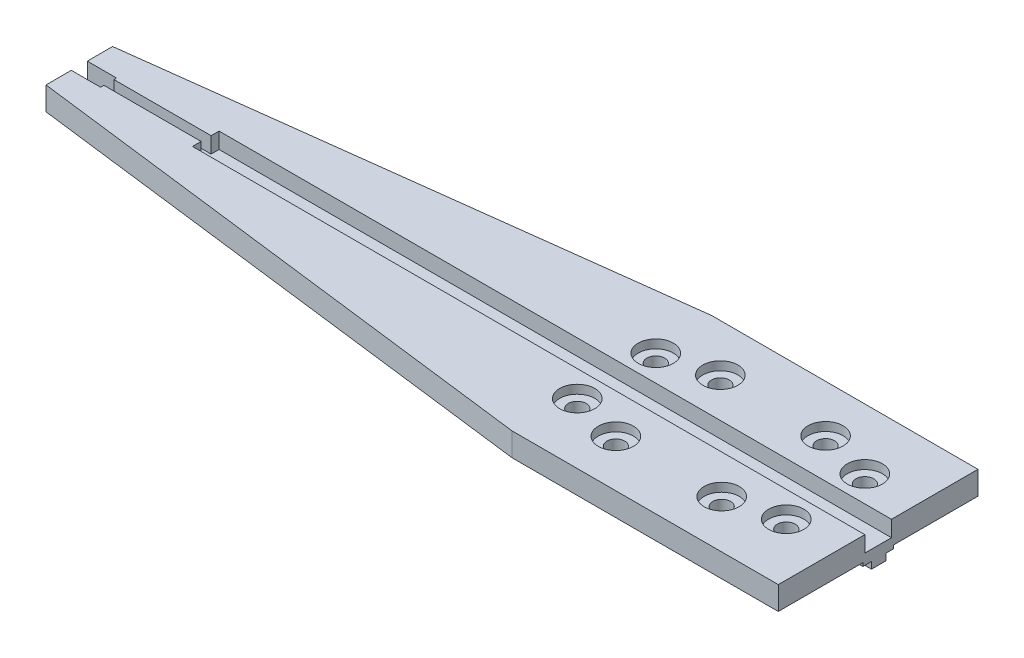
SolidWorks part; units mm, degrees
ref_plane "Front Plane" through (0, 0, 0) normal (0, 0, 1) x (1, 0, 0)
ref_plane "Top Plane" through (0, 0, 0) normal (0, 1, 0) x (1, 0, 0)
ref_plane "Right Plane" through (0, 0, 0) normal (1, 0, 0) x (0, 0, -1)
sketch "Sketch2" plane through (0, 0, 0) normal (1, 0, 0) x (0, 0, -1)
  line L1 (-19.05, 3.175) -> (19.05, 3.175)
  line L2 (-19.05, 3.175) -> (-19.05, -3.175)
  line L3 (-19.05, -3.175) -> (19.05, -3.175)
  line L4 (19.05, 3.175) -> (19.05, -3.175)
  dimension "D1" = 38.1
  dimension "D2" = 6.35
  dimension "D3" = 3.175
  dimension "D4" = 19.05
extrude "Boss-Extrude1" add sketch "Sketch2" along normal blind 152.4
hole_wizard "CBORE for M3 SBHCS1" positions "Sketch5" profile "Sketch6" counterbore size "M3" standard "ANSI Metric" end condition through all
sketch "Sketch5" plane through (0, 3.175, 0) normal (0, 1, 0) x (1, 0, 0)
  line L0 (152.4, 19.05) -> (152.4, -19.05) construction
  line L1 (152.4, 19.05) -> (0, 19.05) construction
  line L2 (152.4, -19.05) -> (0, -19.05) construction
  point P0 (142.367, -7.493)
  point P2 (142.367, 7.493)
  point P9 (102.489, 7.493)
  point P11 (102.489, -7.493)
  point P18 (132.334, 10.033)
  point P20 (112.268, 10.0326)
  point P22 (112.3954, -10.033)
  point P24 (132.461, -9.906)
  point P31 (112.9282, -3.9408)
  dimension "D1" = 14.986
  dimension "D2" = 10.033
  dimension "D3" = 10.033
  dimension "D4" = 39.878
  dimension "D5" = 39.878
  dimension "D6" = 14.986
  dimension "D7" = 11.557
  dimension "D8" = 11.557
  dimension "D9" = 20.066
  dimension "D10" = 19.939
  dimension "D11" = 20.066
  dimension "D12" = 20.066
  dimension "D13" = 20.066
  dimension "D14" = 9.017
  dimension "D15" = 9.144
  dimension "D16" = 9.017
  dimension "D17" = 9.017
sketch "Sketch6" plane through (142.367, 3.175, 7.493) normal (1, 0, 0) x (0, 0, 1)
  line L0 (0, 0) -> (0, 6.35)
  line L1 (0, 6.35) -> (1.7, 6.35)
  line L3 (1.7, 6.35) -> (1.7, 1.65)
  line L4 (1.7, 1.65) -> (3.35, 1.65)
  line L5 (3.35, 1.65) -> (3.35, 0)
  line L7 (3.35, 0) -> (0, 0)
  line L11 (0, -6.35) -> (0, 107.95) construction
  dimension "Thru Hole Dia." = 3.4
  dimension "Thru Hole Depth" = 6.35
  dimension "C'Bore Dia." = 6.7
  dimension "C'Bore Depth" = 1.65
sketch "Sketch9" plane through (0, 0, 0) normal (-1, 0, 0) x (0, 0, 1)
  line L0 (-1.524, 3.175) -> (-1.524, 0.127)
  line L1 (-19.05, 3.175) -> (19.05, 3.175) construction
  line L2 (-1.524, 0.127) -> (1.524, 0.127)
  line L3 (1.524, 0.127) -> (1.524, 3.175)
  line L4 (1.524, 3.175) -> (-1.524, 3.175)
  dimension "D1" = 3.048
  dimension "D2" = 1.524
  dimension "D3" = 3.048
extrude "Cut-Extrude1" cut sketch "Sketch9" against normal blind 5.588
sketch "Sketch12" plane through (0, 3.175, 0) normal (0, 1, 0) x (1, 0, 0)
  line L0 (24.13, 2.54) -> (152.4, 2.54)
  line L1 (152.4, 2.54) -> (152.4, -2.54)
  line L2 (152.4, -2.54) -> (24.13, -2.54)
  line L3 (24.13, -2.54) -> (24.13, 2.54)
  line L6 (0, 0) -> (24.13, 0) construction
  point P7 (24.13, 0)
  dimension "D1" = 2.54
  dimension "D2" = 128.27
  dimension "D3" = 24.13
extrude "Cut-Extrude2" cut sketch "Sketch12" against normal blind 3.048
sketch "Sketch13" plane through (0, 3.175, 0) normal (0, 1, 0) x (1, 0, 0)
  line L0 (5.588, 1.016) -> (24.13, 1.016)
  line L1 (5.588, -1.524) -> (5.588, 1.524) construction
  line L2 (24.13, 2.54) -> (24.13, -2.54) construction
  line L3 (24.13, 1.016) -> (24.13, -0.889)
  line L4 (24.13, -0.889) -> (5.588, -0.889)
  line L5 (5.588, 1.524) -> (5.588, -1.524) construction
  line L6 (5.588, -0.889) -> (5.588, 1.016)
  line L7 (0, 0) -> (152.4, 0) construction
  line L8 (152.4, -2.54) -> (152.4, 2.54) construction
  dimension "D1" = 1.905
  dimension "D2" = 1.016
extrude "Cut-Extrude3" cut sketch "Sketch13" against normal blind 3.048
sketch "Sketch14" plane through (0, 3.175, 0) normal (0, 1, 0) x (1, 0, 0)
  line L5 (0, 6.35) -> (0, 19.05)
  line L6 (0, 19.05) -> (0, 1.524) construction
  line L7 (0, 19.05) -> (101.6, 19.05)
  line L8 (152.4, 19.05) -> (0, 19.05) construction
  line L9 (0, 6.35) -> (101.6, 19.05)
  dimension "D1" = 101.6
  dimension "D2" = 12.7
extrude "Cut-Extrude4" cut sketch "Sketch14" against normal blind 6.35
sketch "Sketch15" plane through (0, 3.175, 0) normal (0, 1, 0) x (1, 0, 0)
  line L0 (0, -6.35) -> (101.6, -19.05)
  line L1 (0, -1.524) -> (0, -19.05) construction
  line L2 (152.4, -19.05) -> (0, -19.05) construction
  line L3 (101.6, -19.05) -> (0, -19.05)
  line L4 (0, -19.05) -> (0, -6.35)
  dimension "D1" = 101.6
  dimension "D2" = 12.7
extrude "Cut-Extrude5" cut sketch "Sketch15" against normal blind 6.35
sketch "Sketch17" plane through (152.4, 0, 0) normal (1, 0, 0) x (0, 0, -1)
  line L0 (-19.05, -1.27) -> (-2.921, -1.27)
  line L1 (-19.05, 3.175) -> (-19.05, -3.175) construction
  line L2 (-2.921, -1.27) -> (-2.921, -1.905)
  line L3 (-2.921, -1.905) -> (-1.27, -1.905)
  line L4 (-1.27, -1.905) -> (-1.27, -3.175)
  line L5 (-19.05, -3.175) -> (19.05, -3.175) construction
  line L6 (-1.27, -3.175) -> (1.524, -3.175)
  line L7 (1.524, -3.175) -> (1.524, -1.905)
  line L8 (1.524, -1.905) -> (2.921, -1.905)
  line L9 (2.921, -1.905) -> (2.921, -1.27)
  line L10 (2.921, -1.27) -> (19.05, -1.27)
  line L11 (19.05, -3.175) -> (19.05, 3.175) construction
  dimension "D1" = 1.905
  dimension "D2" = 1.905
  dimension "D3" = 1.27
  dimension "D4" = 1.27
  dimension "D5" = 2.794
  dimension "D6" = 5.842
  dimension "D7" = 1.397
  dimension "D8" = 17.526
extrude "Cut-Extrude7" cut sketch "Sketch17" against normal blind 59.944 and the other way through all flip side to cut
sketch "Sketch19" plane through (0, 0, 0) normal (-1, 0, 0) x (0, 0, 1)
  line L0 (-19.05, -1.27) -> (19.05, -1.27)
  line L1 (19.05, -1.27) -> (19.05, -3.302)
  line L2 (19.05, -3.302) -> (-19.05, -3.302)
  line L3 (-19.05, -3.302) -> (-19.05, -1.27)
  dimension "D1" = 2.032
extrude "Cut-Extrude9" cut sketch "Sketch19" against normal blind 92.456
